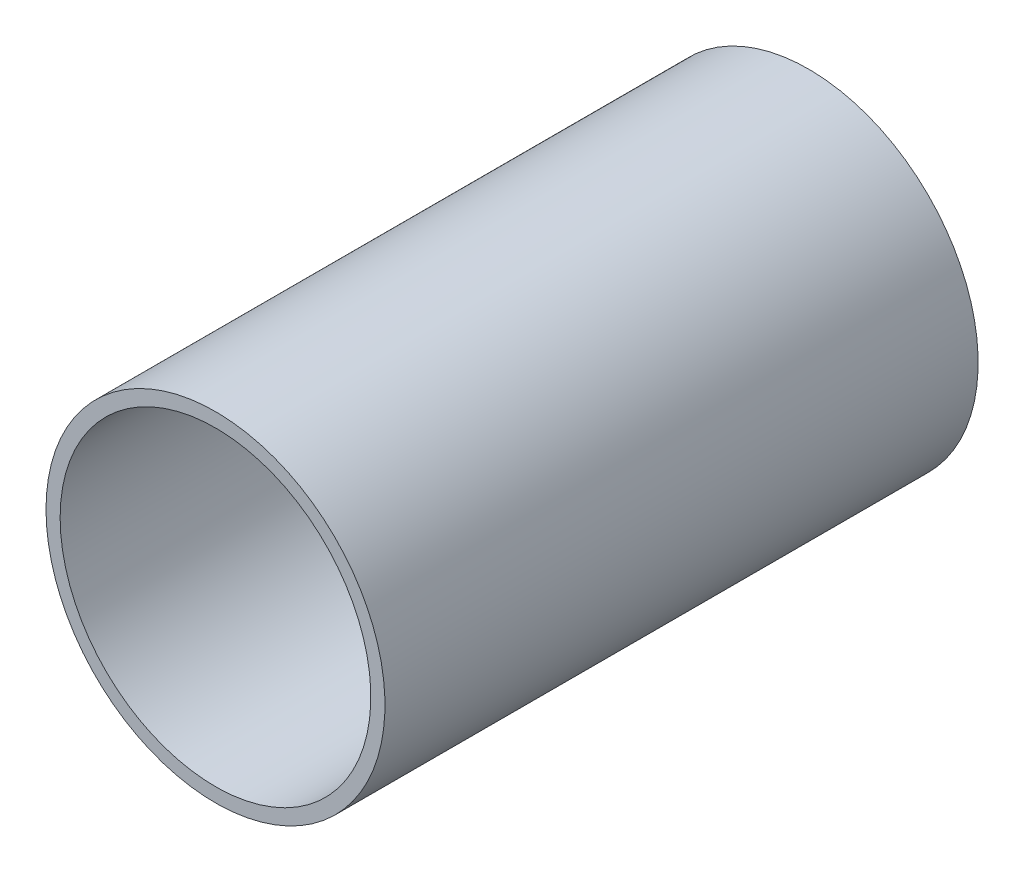
SolidWorks part; units mm, degrees
ref_plane "Front Plane" through (0, 0, 0) normal (0, 0, 1) x (1, 0, 0)
ref_plane "Top Plane" through (0, 0, 0) normal (0, 1, 0) x (1, 0, 0)
ref_plane "Right Plane" through (0, 0, 0) normal (1, 0, 0) x (0, 0, -1)
sketch "Sketch1" plane through (0, 0, 0) normal (0, 0, 1) x (1, 0, 0)
  line L0 (0, 0) -> (0, 26789.2249) construction
  line L1 (0, 0) -> (26789.2249, 0) construction
  circle A0 centre (0, 0) radius 12
  circle A1 centre (0, 0) radius 11
  dimension "D1" = 24
  dimension "D2" = 22
extrude "Boss-Extrude1" add sketch "Sketch1" along normal mid plane 42
